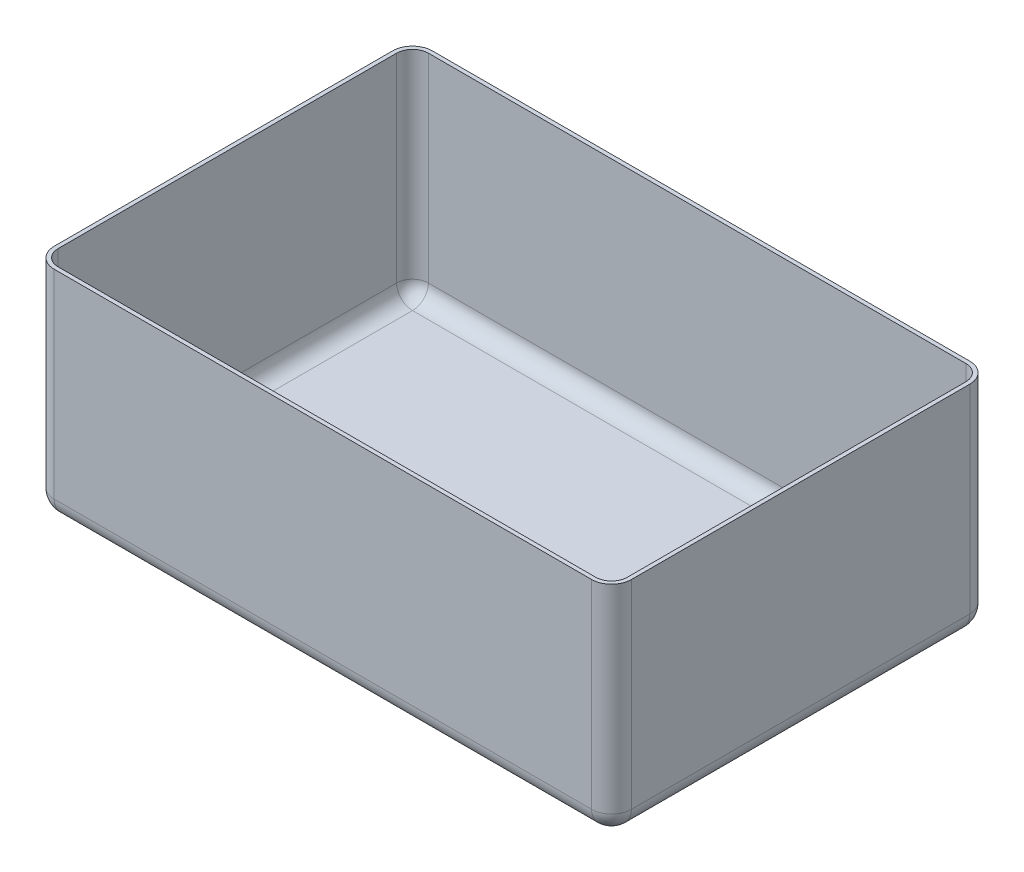
SolidWorks part; units mm, degrees
ref_plane "Front Plane" through (0, 0, 0) normal (0, 0, 1) x (1, 0, 0)
ref_plane "Top Plane" through (0, 0, 0) normal (0, 1, 0) x (1, 0, 0)
ref_plane "Right Plane" through (0, 0, 0) normal (1, 0, 0) x (0, 0, -1)
sketch "Sketch1" plane through (0, 0, 0) normal (0, 1, 0) x (1, 0, 0)
  line L1 (-184.15, -120.65) -> (184.15, -120.65)
  line L2 (-184.15, -120.65) -> (-184.15, 120.65)
  line L3 (-184.15, 120.65) -> (184.15, 120.65)
  line L4 (184.15, -120.65) -> (184.15, 120.65)
  line L5 (-184.15, -120.65) -> (184.15, 120.65) construction
  line L6 (-184.15, 120.65) -> (184.15, -120.65) construction
  point P0 (0, 0)
  dimension "D1" = 241.3
  dimension "D2" = 368.3
extrude "Boss-Extrude1" add sketch "Sketch1" along normal blind 139.7
fillet "Fillet1" radius 12.7 8 edges at (0, 0, -120.65) (-184.15, 0, 0) (0, 0, 120.65) (184.15, 0, 0) (184.15, 69.85, -120.65) (184.15, 69.85, 120.65) (-184.15, 69.85, -120.65) (-184.15, 69.85, 120.65)
shell "Shell1" thickness 2.54
